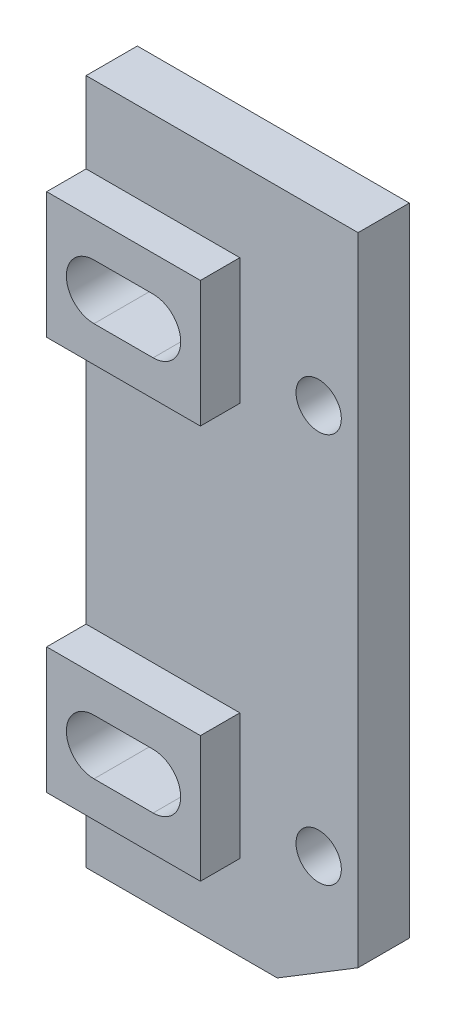
SolidWorks part; units mm, degrees
ref_plane "前视基准面" through (0, 0, 0) normal (0, 0, 1) x (1, 0, 0)
ref_plane "上视基准面" through (0, 0, 0) normal (0, 1, 0) x (1, 0, 0)
ref_plane "右视基准面" through (0, 0, 0) normal (1, 0, 0) x (0, 0, -1)
other "Configuration Table"
sketch "Opposite end crossbar with two adjustable through slots profile" plane through (0, 0, 0) normal (0, 0, 1) x (1, 0, 0)
  line L0 (25, -24) -> (34.7, -24)
  line L1 (34.7, -24) -> (38.8, -21.5)
  line L2 (38.8, -21.5) -> (38.8, 10.8)
  line L3 (38.8, 10.8) -> (25, 10.8)
  line L4 (25, 10.8) -> (25, -24)
  line L5 (27.4, -17.9) -> (30.4, -17.9)
  line L6 (30.4, -15.1) -> (27.4, -15.1)
  line L7 (27.4, 2.1) -> (30.4, 2.1)
  line L8 (30.4, 4.9) -> (27.4, 4.9)
  circle A0 centre (36.8, -17.6) radius 1.15
  circle A1 centre (36.8, 2.2) radius 1.15
  arc A2 (30.4, -17.9) -> (30.4, -15.1) centre (30.4, -16.5) ccw
  arc A3 (27.4, -15.1) -> (27.4, -17.9) centre (27.4, -16.5) ccw
  arc A4 (30.4, 2.1) -> (30.4, 4.9) centre (30.4, 3.5) ccw
  arc A5 (27.4, 4.9) -> (27.4, 2.1) centre (27.4, 3.5) ccw
extrude "Opposite end crossbar with two adjustable through slots" add sketch "Opposite end crossbar with two adjustable through slots profile" along normal blind 2.6
sketch "Two raised PCB bolt pads profile" plane through (0, 0, 0) normal (0, 0, 1) x (1, 0, 0)
  line L0 (25, -19.7) -> (32.8, -19.7)
  line L1 (32.8, -19.7) -> (32.8, -13.3)
  line L2 (32.8, -13.3) -> (25, -13.3)
  line L3 (25, -13.3) -> (25, -19.7)
  line L4 (25, 0.3) -> (32.8, 0.3)
  line L5 (32.8, 0.3) -> (32.8, 6.7)
  line L6 (32.8, 6.7) -> (25, 6.7)
  line L7 (25, 6.7) -> (25, 0.3)
  line L8 (27.4, -17.9) -> (30.4, -17.9)
  line L9 (30.4, -15.1) -> (27.4, -15.1)
  line L10 (27.4, 2.1) -> (30.4, 2.1)
  line L11 (30.4, 4.9) -> (27.4, 4.9)
  arc A0 (30.4, -17.9) -> (30.4, -15.1) centre (30.4, -16.5) ccw
  arc A1 (27.4, -15.1) -> (27.4, -17.9) centre (27.4, -16.5) ccw
  arc A2 (30.4, 2.1) -> (30.4, 4.9) centre (30.4, 3.5) ccw
  arc A3 (27.4, 4.9) -> (27.4, 2.1) centre (27.4, 3.5) ccw
extrude "Two raised PCB bolt pads" add sketch "Two raised PCB bolt pads profile" along normal blind 2 from offset 2.6
